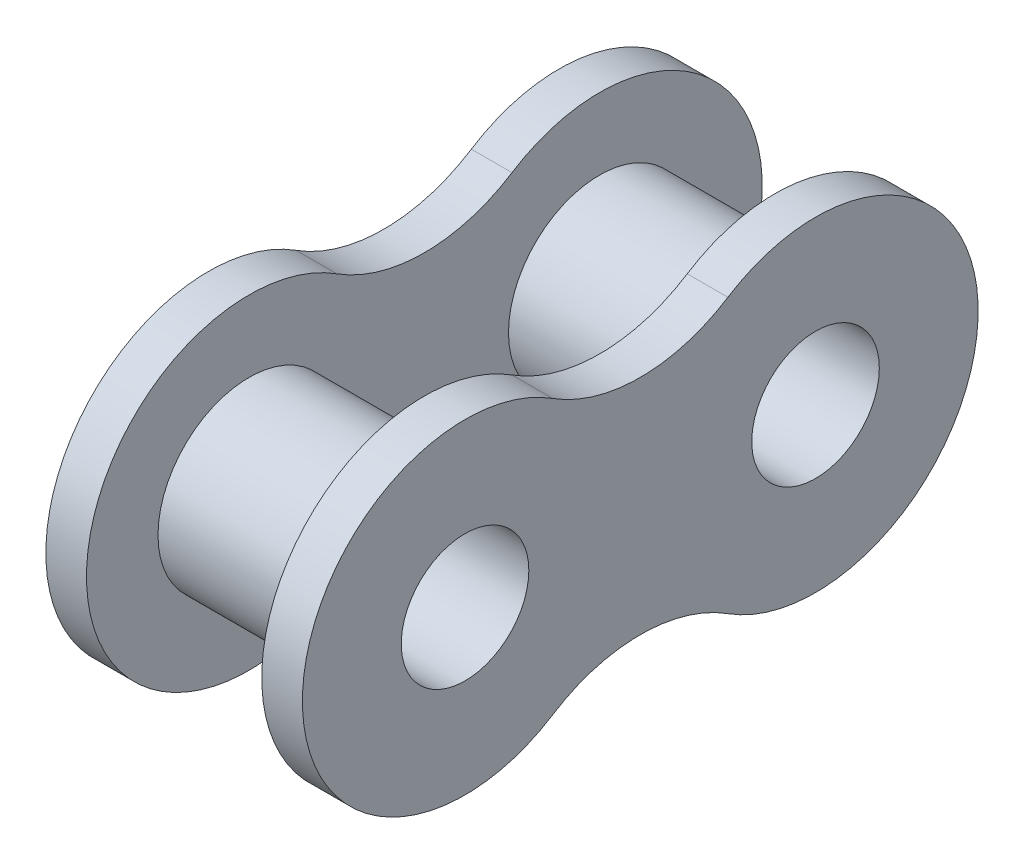
SolidWorks part; units mm, degrees
ref_plane "Front Plane" through (0, 0, 0) normal (0, 0, 1) x (1, 0, 0)
ref_plane "Top Plane" through (0, 0, 0) normal (0, 1, 0) x (1, 0, 0)
ref_plane "Right Plane" through (0, 0, 0) normal (1, 0, 0) x (0, 0, -1)
sketch "Sketch1" plane through (0, 0, 0) normal (1, 0, 0) x (0, 0, -1)
  line L0 (0, 0) -> (6.35, 0) construction
  arc A0 (1.5875, 2.4822) -> (1.5875, -2.4822) centre (0, 0) ccw
  arc A1 (4.7625, -2.4822) -> (4.7625, 2.4822) centre (6.35, 0) ccw
  circle A2 centre (0, 0) radius 1.1557
  circle A3 centre (6.35, 0) radius 1.1557
  arc A4 (1.5875, 2.4822) -> (4.7625, 2.4822) centre (3.175, 4.9643) ccw
  arc A5 (1.5875, -2.4822) -> (4.7625, -2.4822) centre (3.175, -4.9643) cw
  point P9 (3.175, 0)
  dimension "D1" = 5.8928
  dimension "D3" = 2.3114
  dimension "D2" = 6.35
extrude "Boss-Extrude1" add sketch "Sketch1" along normal blind 0.7366
sketch "Sketch2" plane through (0.7366, 0, 0) normal (1, 0, 0) x (0, 0, -1)
  circle A0 centre (0, 0) radius 1.1557
  circle A1 centre (0, 0) radius 1.651
  circle A2 centre (6.35, 0) radius 1.1557
  circle A3 centre (6.35, 0) radius 1.651
  circle A4 centre (0, 0) radius 1.1557 construction
  dimension "D1" = 3.302
extrude "Boss-Extrude2" add sketch "Sketch2" along normal blind 3.175
ref_plane "Plane1" through (2.3241, 0, 0) normal (1, 0, 0) x (0, 0, -1)
mirror "Mirror1" about plane through (2.3241, 0, 0) normal (1, 0, 0) of "Boss-Extrude1"
